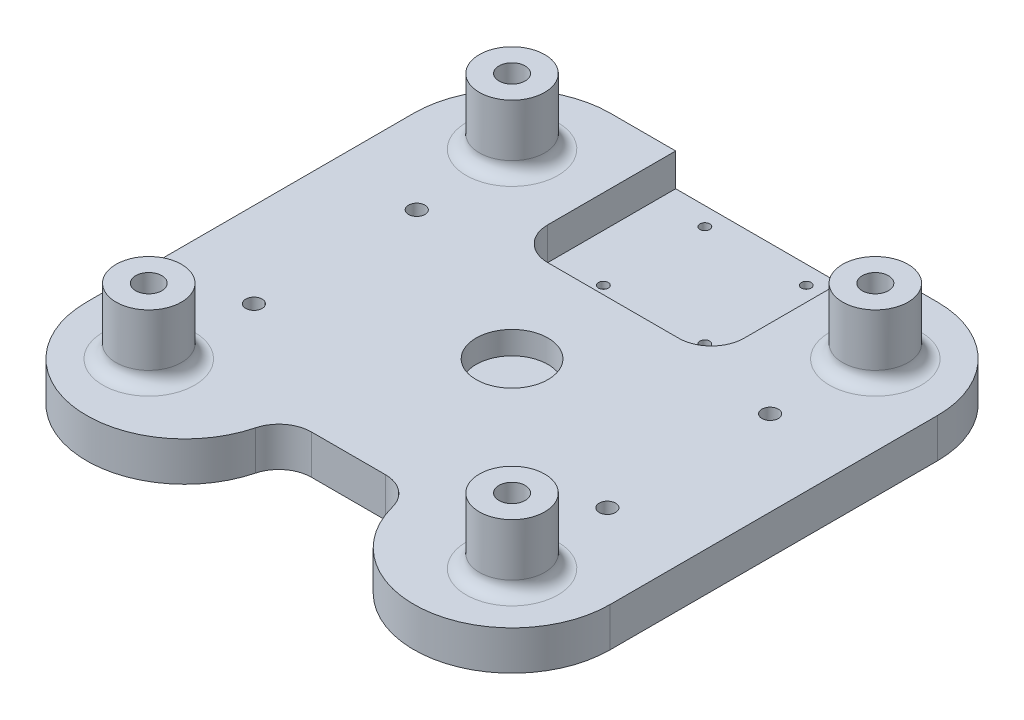
SolidWorks part; units mm, degrees
other "Camera1"
ref_plane "Front Plane" through (0, 0, 0) normal (0, 0, 1) x (1, 0, 0)
ref_plane "Top Plane" through (0, 0, 0) normal (0, 1, 0) x (1, 0, 0)
ref_plane "Right Plane" through (0, 0, 0) normal (1, 0, 0) x (0, 0, -1)
sketch "Sketch12" plane through (0, 0, 0) normal (0, 1, 0) x (1, 0, 0)
  line L0 (-20, -50) -> (20, -50)
  line L1 (-50, 80) -> (50, 80)
  line L2 (-80, 50) -> (-80, -50)
  line L4 (80, 50) -> (80, -50)
  line L5 (-80, 80) -> (80, -80) construction
  line L6 (-80, -80) -> (80, 80) construction
  arc A0 (50, -80) -> (80, -50) centre (50, -50) ccw
  arc A1 (-80, -50) -> (-50, -80) centre (-50, -50) ccw
  arc A2 (50, 80) -> (80, 50) centre (50, 50) cw
  arc A3 (-50, 80) -> (-80, 50) centre (-50, 50) ccw
  arc A4 (-50, -80) -> (-20, -50) centre (-50, -50) ccw
  arc A5 (50, -80) -> (20, -50) centre (50, -50) cw
  point P0 (0, 0)
  dimension "D1" = 30
extrude "Boss-Extrude6" add sketch "Sketch12" along normal blind 12
fillet "Fillet4" radius 10 2 edges at (20, 6, 50) (-20, 6, 50)
sketch "Sketch13" plane through (0, 12, 0) normal (0, 1, 0) x (1, 0, 0)
  line L1 (-55.5, 55.5) -> (55.5, 55.5) construction
  line L2 (-55.5, 55.5) -> (-55.5, -55.5) construction
  line L3 (-55.5, -55.5) -> (55.5, -55.5) construction
  line L4 (55.5, 55.5) -> (55.5, -55.5) construction
  line L5 (-55.5, 55.5) -> (55.5, -55.5) construction
  line L6 (-55.5, -55.5) -> (55.5, 55.5) construction
  circle A0 centre (-55.5, 55.5) radius 4
  circle A1 centre (55.5, 55.5) radius 4
  circle A2 centre (-55.5, -55.5) radius 4
  circle A3 centre (55.5, -55.5) radius 4
  point P0 (0, 0)
extrude "Cut-Extrude5" cut sketch "Sketch13" against normal through all
sketch "Sketch14" plane through (0, 12, 0) normal (0, 1, 0) x (1, 0, 0)
  circle A2 centre (-55.5, 55.5) radius 10
  circle A3 centre (-55.5, 55.5) radius 10
  circle A8 centre (55.5, 55.5) radius 10
  circle A9 centre (55.5, 55.5) radius 10
  circle A11 centre (-55.5, -55.5) radius 10
  circle A12 centre (-55.5, -55.5) radius 10
  circle A14 centre (55.5, -55.5) radius 10
  circle A15 centre (55.5, -55.5) radius 10
  dimension "D1" = 6
  dimension "D2" = 6
  dimension "D3" = 6
  dimension "D4" = 6
extrude "Boss-Extrude7" add sketch "Sketch14" along normal blind 20
sketch "Sketch15" plane through (0, 12, 0) normal (0, -1, 0) x (1, 0, 0)
  circle A1 centre (-55.5, -55.5) radius 4
  circle A2 centre (-55.5, -55.5) radius 4
  circle A3 centre (-55.5, 55.5) radius 4
  circle A4 centre (-55.5, 55.5) radius 4
  circle A5 centre (55.5, 55.5) radius 4
  circle A6 centre (55.5, 55.5) radius 4
  circle A7 centre (55.5, -55.5) radius 4
  circle A8 centre (55.5, -55.5) radius 4
  dimension "D1" = 0
  dimension "D2" = 0
  dimension "D3" = 0
  dimension "D4" = 0
extrude "Cut-Extrude6" cut sketch "Sketch15" against normal through all
fillet "Fillet5" radius 4 4 edges at (-55.5, 12, -65.5) (55.5, 12, -65.5) (55.5, 12, 45.5) (-55.5, 12, 45.5)
sketch "Sketch16" plane through (0, 12, 0) normal (0, 1, 0) x (1, 0, 0)
  circle A0 centre (0, 0) radius 11
extrude "Cut-Extrude7" cut sketch "Sketch16" against normal blind 7
sketch "Sketch17" plane through (0, 12, 0) normal (0, 1, 0) x (1, 0, 0)
  line L1 (-15.5, 74.4) -> (15.5, 74.4) construction
  line L2 (-15.5, 74.4) -> (-15.5, 43.4) construction
  line L3 (-15.5, 43.4) -> (15.5, 43.4) construction
  line L4 (15.5, 74.4) -> (15.5, 43.4) construction
  line L5 (-15.5, 74.4) -> (15.5, 43.4) construction
  line L6 (-15.5, 43.4) -> (15.5, 74.4) construction
  circle A0 centre (-15.5, 74.4) radius 1.5
  circle A1 centre (15.5, 74.4) radius 1.5
  circle A2 centre (-15.5, 43.4) radius 1.5
  circle A3 centre (15.5, 43.4) radius 1.5
  point P0 (0, 58.9)
  dimension "D1" = 58.9
extrude "Cut-Extrude8" cut sketch "Sketch17" against normal through all
sketch "Sketch18" plane through (0, 12, 0) normal (0, 1, 0) x (1, 0, 0)
  line L0 (-30, 30.9) -> (30, 30.9)
  line L1 (-15.5, 74.4) -> (15.5, 43.4) construction
  line L2 (-30, 30.9) -> (-30, 100.9)
  line L3 (-30, 100.9) -> (30, 100.9)
  line L4 (30, 100.9) -> (30, 30.9)
  point P3 (0, 30.9)
  point P7 (0, 58.9)
  dimension "D1" = 28
extrude "Cut-Extrude9" cut sketch "Sketch18" against normal blind 10
fillet "Fillet6" radius 10 2 edges at (30, 7, -30.9) (-30, 7, -30.9)
sketch "Sketch19" plane through (0, 12, 0) normal (0, 1, 0) x (1, 0, 0)
  line L1 (-53.99, 24.8675) -> (53.99, 24.8675) construction
  line L2 (-53.99, 24.8675) -> (-53.99, -24.8675) construction
  line L3 (-53.99, -24.8675) -> (53.99, -24.8675) construction
  line L4 (53.99, 24.8675) -> (53.99, -24.8675) construction
  line L5 (-53.99, 24.8675) -> (53.99, -24.8675) construction
  line L6 (-53.99, -24.8675) -> (53.99, 24.8675) construction
  circle A0 centre (-53.99, 24.8675) radius 2.5
  circle A1 centre (-53.99, -24.8675) radius 2.5
  circle A2 centre (53.99, 24.8675) radius 2.5
  circle A3 centre (53.99, -24.8675) radius 2.5
  point P0 (0, 0)
extrude "Cut-Extrude10" cut sketch "Sketch19" against normal through all
